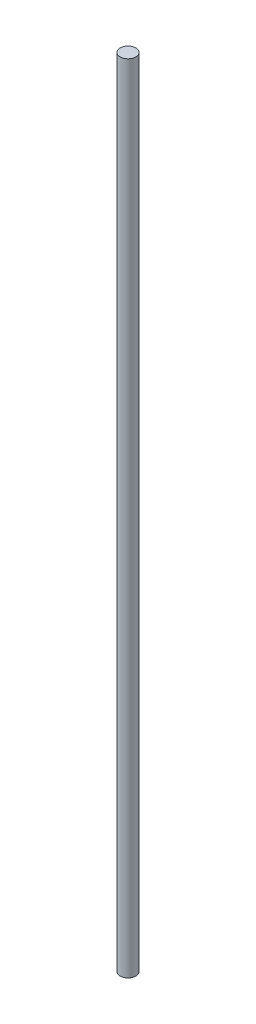
SolidWorks part; units mm, degrees
ref_plane "前视基准面" through (0, 0, 0) normal (0, 0, 1) x (1, 0, 0)
ref_plane "上视基准面" through (0, 0, 0) normal (0, 1, 0) x (1, 0, 0)
ref_plane "右视基准面" through (0, 0, 0) normal (1, 0, 0) x (0, 0, -1)
sketch "草图1" plane through (0, 0, 0) normal (0, 1, 0) x (1, 0, 0)
  circle A0 centre (0, 0) radius 5
  dimension "D1" = 10
extrude "凸台-拉伸1" add sketch "草图1" along normal blind 508
